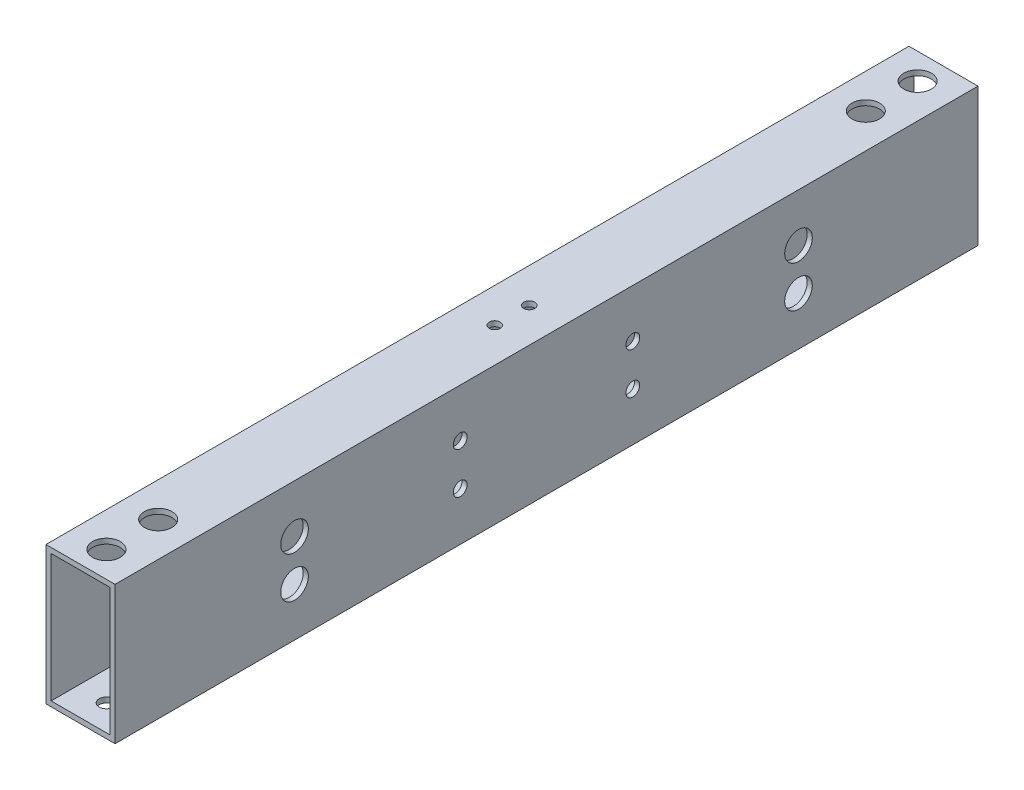
SolidWorks part; units mm, degrees
ref_plane "前视基准面" through (0, 0, 0) normal (0, 0, 1) x (1, 0, 0)
ref_plane "上视基准面" through (0, 0, 0) normal (0, 1, 0) x (1, 0, 0)
ref_plane "右视基准面" through (0, 0, 0) normal (1, 0, 0) x (0, 0, -1)
sketch "草图1" plane through (0, 0, 0) normal (0, 0, 1) x (1, 0, 0)
  line L1 (-10, -20) -> (10, -20)
  line L2 (-10, -20) -> (-10, 20)
  line L3 (-10, 20) -> (10, 20)
  line L4 (10, -20) -> (10, 20)
  line L5 (-10, -20) -> (10, 20) construction
  line L6 (-10, 20) -> (10, -20) construction
  line L7 (-8.5, -18.5) -> (8.5, -18.5)
  line L8 (-8.5, -18.5) -> (-8.5, 18.5)
  line L9 (-8.5, 18.5) -> (8.5, 18.5)
  line L10 (8.5, -18.5) -> (8.5, 18.5)
  line L11 (-8.5, -18.5) -> (8.5, 18.5) construction
  line L12 (-8.5, 18.5) -> (8.5, -18.5) construction
  point P0 (0, 0)
  point P5 (0, 0)
  dimension "D1" = 40
  dimension "D2" = 20
  dimension "D3" = 37
  dimension "D4" = 17
extrude "凸台-拉伸1" add sketch "草图1" against normal blind 250
sketch "草图2" plane through (-10, 0, 0) normal (-1, 0, 0) x (0, 0, 1)
  line L0 (-125, 20) -> (-125, -49980) construction
  line L1 (-250, 20) -> (0, 20) construction
  line L2 (0, 20) -> (0, -20) construction
  line L3 (-100, 6) -> (-52, 6) construction
  line L4 (-100, 6) -> (-100, -6) construction
  line L5 (-100, -6) -> (-52, -6) construction
  line L6 (-52, 6) -> (-52, -6) construction
  line L11 (-76, 6) -> (-76, -6) construction
  line L12 (-100, 0) -> (-52, 0) construction
  line L13 (-150, 0) -> (-198, 0) construction
  line L14 (-174, 6) -> (-174, -6) construction
  line L15 (-198, 6) -> (-198, -6) construction
  line L16 (-150, -6) -> (-198, -6) construction
  line L17 (-150, 6) -> (-150, -6) construction
  line L18 (-150, 6) -> (-198, 6) construction
  circle A0 centre (-100, 6) radius 2
  circle A8 centre (-52, 6) radius 2
  circle A9 centre (-52, -6) radius 2
  circle A10 centre (-100, -6) radius 2
  circle A11 centre (-150, -6) radius 2
  circle A12 centre (-198, -6) radius 2
  circle A13 centre (-198, 6) radius 2
  circle A14 centre (-150, 6) radius 2
  point P4 (-125, 20)
  point P25 (-76, 0)
  dimension "D4" = 4
  dimension "D1" = 12
  dimension "42" = 48
  dimension "D3" = 20
  dimension "70" = 52
extrude "切除-拉伸1" cut sketch "草图2" against normal through all
sketch "草图3" plane through (0, 20, 0) normal (0, 1, 0) x (1, 0, 0)
  line L0 (-10, 30) -> (49990, 30) construction
  line L2 (10, 0) -> (-10, 0) construction
  line L3 (0, 0) -> (0, 50000) construction
  line L4 (10, 125) -> (50010, 125) construction
  line L5 (10, 250) -> (10, 0) construction
  circle A0 centre (0, 22.5) radius 2.1
  circle A1 centre (0, 7.5) radius 2.1
  circle A2 centre (0, 242.5) radius 2.1
  circle A3 centre (0, 227.5) radius 2.1
  point P6 (0, 0)
  point P15 (10, 125)
  dimension "D2" = 4.2
  dimension "D3" = 4.2
  dimension "D1" = 30
  dimension "D4" = 15
  dimension "D5" = 7.5
extrude "切除-拉伸2" cut sketch "草图3" against normal through all
sketch "草图4" plane through (0, 20, 0) normal (0, 1, 0) x (1, 0, 0)
  line L0 (0, 250) -> (0, -49750) construction
  line L1 (10, 250) -> (-10, 250) construction
  line L2 (-10, 125) -> (49990, 125) construction
  line L3 (-10, 250) -> (-10, 0) construction
  circle A0 centre (0, 130) radius 1.6
  circle A1 centre (0, 120) radius 1.6
  point P4 (0, 250)
  point P9 (-10, 125)
  dimension "D1" = 3.2
  dimension "D2" = 10
extrude "切除-拉伸3" cut sketch "草图4" against normal through all
sketch "草图5" plane through (0, 20, 0) normal (0, 1, 0) x (1, 0, 0)
  line L0 (-10, 125) -> (49990, 125) construction
  line L1 (-10, 250) -> (-10, 0) construction
  line L2 (10, 250) -> (10, 0) construction
  circle A0 centre (0, 22.5) radius 4
  circle A1 centre (0, 7.5) radius 4
  circle A2 centre (0, 242.5) radius 4
  circle A3 centre (0, 227.5) radius 4
  point P10 (-10, 125)
  point P13 (10, 125)
  dimension "D1" = 8
  dimension "D2" = 8
extrude "切除-拉伸4" cut sketch "草图5" against normal blind 10
sketch "草图6" plane through (10, 0, 0) normal (1, 0, 0) x (0, 0, -1)
  circle A0 centre (52, 6) radius 4
  circle A1 centre (52, -6) radius 4
  circle A2 centre (198, 6) radius 4
  circle A3 centre (198, -6) radius 4
  dimension "D1" = 8
extrude "切除-拉伸5" cut sketch "草图6" against normal blind 10
equation "\"3。2\"=3.21956"
